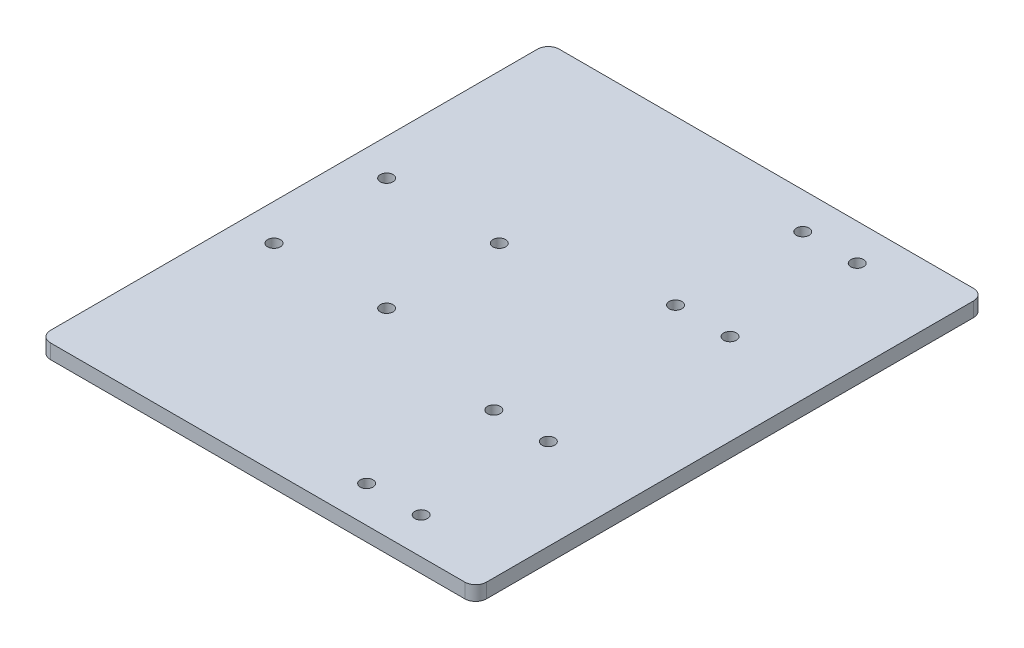
SolidWorks part; units mm, degrees
ref_plane "Front Plane" through (0, 0, 0) normal (0, 0, 1) x (1, 0, 0)
ref_plane "Top Plane" through (0, 0, 0) normal (0, 1, 0) x (1, 0, 0)
ref_plane "Right Plane" through (0, 0, 0) normal (1, 0, 0) x (0, 0, -1)
sketch "Sketch1" plane through (0, 0, 0) normal (0, 1, 0) x (1, 0, 0)
  line L1 (-60, 70) -> (60, 70)
  line L2 (-60, 70) -> (-60, -70)
  line L3 (-60, -70) -> (60, -70)
  line L4 (60, 70) -> (60, -70)
  line L5 (-60, 70) -> (60, -70) construction
  line L6 (-60, -70) -> (60, 70) construction
  circle A0 centre (-50, 15.5) radius 1.75
  circle A1 centre (-19, 15.5) radius 1.75
  circle A2 centre (-50, -15.5) radius 1.75
  circle A3 centre (-19, -15.5) radius 1.75
  circle A4 centre (20, 60) radius 1.75
  circle A5 centre (35, 60) radius 1.75
  circle A6 centre (35, 25) radius 1.75
  circle A7 centre (20, 25) radius 1.75
  circle A8 centre (20, -60) radius 1.75
  circle A9 centre (35, -60) radius 1.75
  circle A10 centre (35, -25) radius 1.75
  circle A11 centre (20, -25) radius 1.75
  point P0 (0, 0)
  dimension "D3" = 3.5
  dimension "D8" = 3.5
  dimension "D11" = 2
  dimension "D13" = 3.5
  dimension "D20" = 38.0789
  dimension "D21" = 3.5
  dimension "D1" = 120
  dimension "D2" = 140
  dimension "D4" = 54.5
  dimension "D5" = 10
  dimension "D7" = 31
  dimension "D9" = 10
  dimension "D10" = 54.5
  dimension "D12" = 31
  dimension "D14" = 10
  dimension "D15" = 80
  dimension "D18" = 35
  dimension "D19" = 15
  dimension "D22" = 10
  dimension "D23" = 80
  dimension "D26" = 35
  dimension "D27" = 15
  dimension "D28" = 38.0789
  dimension "D6" = 2
  dimension "D16" = 2
  dimension "D17" = 2
  dimension "D24" = 2
  dimension "D25" = 2
extrude "Boss-Extrude1" add sketch "Sketch1" along normal blind 4
fillet "Fillet1" radius 3 4 edges at (60, 2, -70) (60, 2, 70) (-60, 2, 70) (-60, 2, -70)
